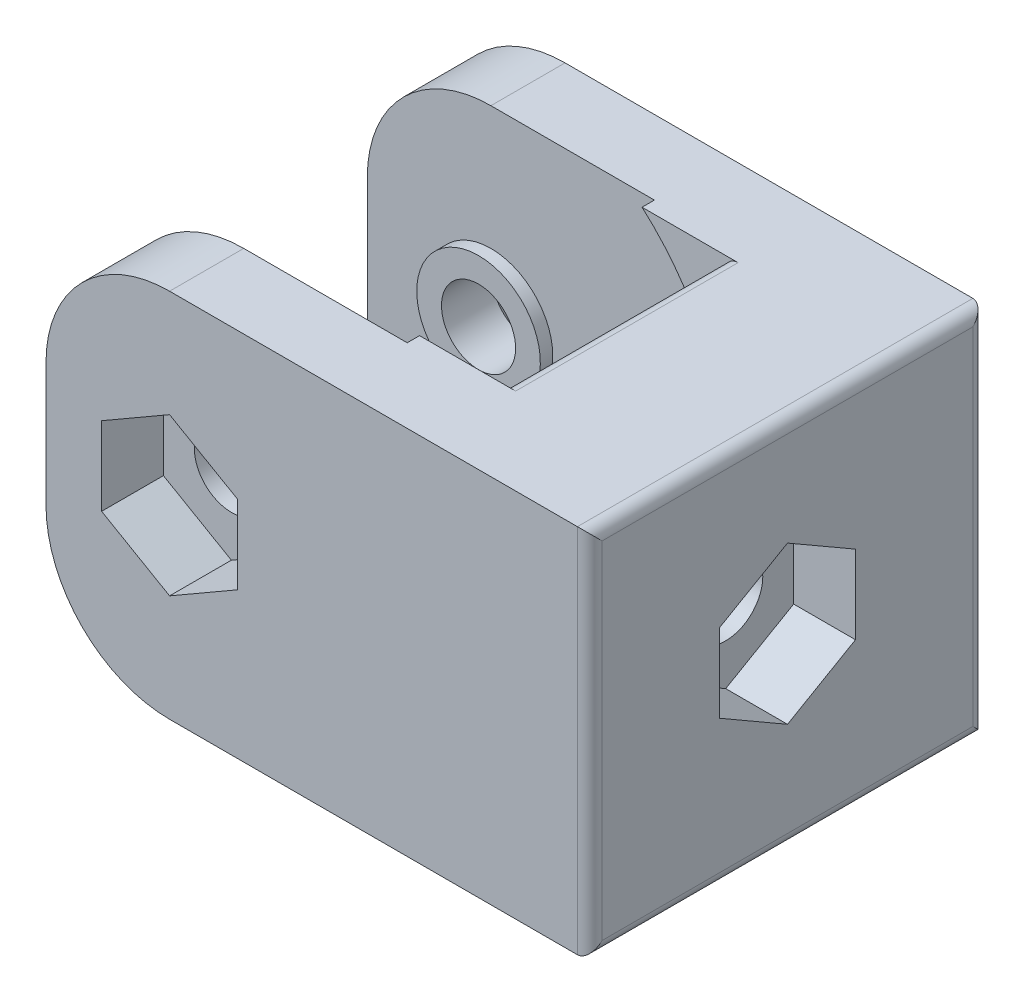
SolidWorks part; units mm, degrees
ref_plane "Front Plane" through (0, 0, 0) normal (0, 0, 1) x (1, 0, 0)
ref_plane "Top Plane" through (0, 0, 0) normal (0, 1, 0) x (1, 0, 0)
ref_plane "Right Plane" through (0, 0, 0) normal (1, 0, 0) x (0, 0, -1)
sketch "Sketch1" plane through (0, 0, 0) normal (0, 0, 1) x (1, 0, 0)
  line L1 (0, 0) -> (-22, 0)
  line L2 (0, 0) -> (0, 15)
  line L3 (0, 15) -> (-22, 15)
  line L4 (-22, 0) -> (-22, 15)
  dimension "D1" = 15
  dimension "D2" = 22
extrude "Boss-Extrude1" add sketch "Sketch1" along normal blind 16
sketch "Sketch2" plane through (0, 0, 16) normal (0, 0, 1) x (1, 0, 0)
  line L0 (0, 0) -> (0, 15) construction
  line L1 (0, 15) -> (-22, 15) construction
  circle A0 centre (-17, 7.5) radius 1.5
  dimension "D1" = 3
  dimension "D2" = 17
  dimension "D3" = 7.5
extrude "Cut-Extrude1" cut sketch "Sketch2" against normal through all
ref_plane "Plane1" through (0, 0, 8) normal (0, 0, 1) x (1, 0, 0)
sketch "Sketch3" plane through (0, 0, 8) normal (0, 0, 1) x (1, 0, 0)
  circle A0 centre (-17, 7.5) radius 10
  circle A1 centre (-17, 7.5) radius 2.5
  dimension "D1" = 20
  dimension "D2" = 5
extrude "Cut-Extrude2" cut sketch "Sketch3" against normal blind 5 and the other way blind 5
sketch "Sketch4" plane through (-22, 0, 0) normal (-1, 0, 0) x (0, 0, 1)
  line L0 (13, 15) -> (3, 15) construction
  line L1 (3.5, 15) -> (12.5, 15)
  line L2 (3.5, 15) -> (3.5, 0)
  line L3 (3.5, 0) -> (12.5, 0)
  line L4 (12.5, 15) -> (12.5, 0)
  line L5 (3, 0) -> (13, 0) construction
  line L6 (3, 0) -> (3, 15) construction
  dimension "D1" = 9
  dimension "D2" = 0.5
extrude "Cut-Extrude3" cut sketch "Sketch4" against normal blind 15
sketch "Sketch9" plane through (0, 0, 0) normal (0, 0, -1) x (-1, 0, 0)
  circle A0 centre (17, 7.5) radius 3.15
  dimension "D1" = 6.3
sketch "Sketch10" plane through (0, 0, 0) normal (1, 0, 0) x (0, 0, -1)
  line L0 (-16, 15) -> (0, 0) construction
  circle A0 centre (-8, 7.5) radius 1.5
  dimension "D1" = 3
extrude "Cut-Extrude5" cut sketch "Sketch10" against normal through all
sketch "Sketch11" plane through (-7, 0, 0) normal (-1, 0, 0) x (0, 0, 1)
  circle A0 centre (8, 7.5) radius 3.15
  dimension "D1" = 6.3
extrude "Cut-Extrude6" cut sketch "Sketch11" against normal blind 1.45 draft 45
sketch "Sketch12" plane through (0, 0, 16) normal (0, 0, 1) x (1, 0, 0)
  line L0 (-17, 7.5) -> (-12, 7.5) construction
  line L1 (-17, 7.5) -> (-14.2504, 9.0875) construction
  line L2 (-14.2504, 9.0875) -> (-17, 10.675)
  line L3 (-17, 10.675) -> (-19.7496, 9.0875)
  line L4 (-19.7496, 9.0875) -> (-19.7496, 5.9125)
  line L5 (-19.7496, 5.9125) -> (-17, 4.325)
  line L6 (-17, 4.325) -> (-14.2504, 5.9125)
  line L7 (-14.2504, 5.9125) -> (-14.2504, 9.0875)
  circle A0 centre (-17, 7.5) radius 3.175 construction
  dimension "D2" = 6.35
  dimension "D1" = 5
  dimension "D3" = 30
sketch "Sketch13" plane through (0, 0, 0) normal (1, 0, 0) x (0, 0, -1)
  line L0 (-8, 7.5) -> (-3, 7.5) construction
  line L1 (-8, 7.5) -> (-5.2504, 9.0875) construction
  line L2 (-5.2504, 9.0875) -> (-8, 10.675)
  line L3 (-8, 10.675) -> (-10.7496, 9.0875)
  line L4 (-10.7496, 9.0875) -> (-10.7496, 5.9125)
  line L5 (-10.7496, 5.9125) -> (-8, 4.325)
  line L6 (-8, 4.325) -> (-5.2504, 5.9125)
  line L7 (-5.2504, 5.9125) -> (-5.2504, 9.0875)
  circle A0 centre (-8, 7.5) radius 3.175 construction
  dimension "D2" = 6.35
  dimension "D1" = 5
  dimension "D3" = 30
extrude "Cut-Extrude8" cut sketch "Sketch13" against normal blind 2.5
fillet "Fillet1" radius 5 4 edges at (-22, 0, 14.5) (-22, 0, 1.5) (-22, 15, 1.5) (-22, 15, 14.5)
fillet "Fillet2" radius 0.5 6 edges at (-7, 15, 8) (-7, 0, 8) (0, 7.5, 16) (0, 0, 8) (0, 7.5, 0) (0, 15, 8)
extrude "Cut-Extrude10" cut sketch "Sketch9" against normal blind 1.45 draft 45
extrude "Cut-Extrude12" cut sketch "Sketch12" against normal blind 2.5 and the other way blind 1
